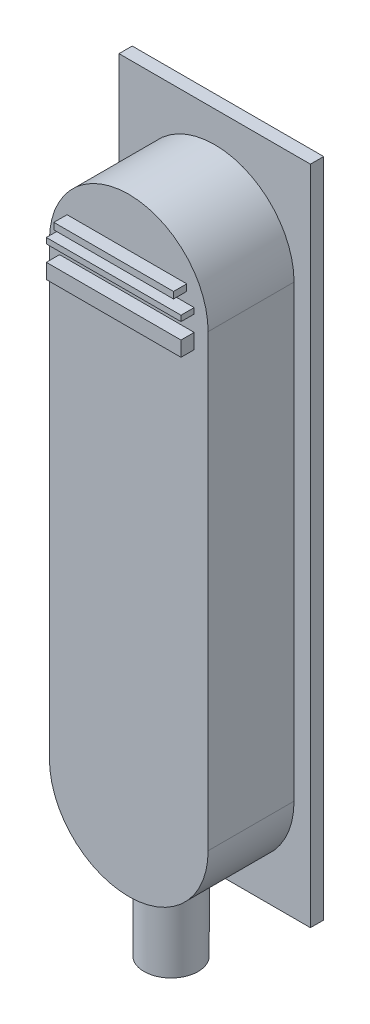
SolidWorks part; units mm, degrees
ref_plane "Front Plane" through (0, 0, 0) normal (0, 0, 1) x (1, 0, 0)
ref_plane "Top Plane" through (0, 0, 0) normal (0, 1, 0) x (1, 0, 0)
ref_plane "Right Plane" through (0, 0, 0) normal (1, 0, 0) x (0, 0, -1)
sketch "Sketch1" plane through (0, 0, 0) normal (0, 0, 1) x (1, 0, 0)
  line L1 (7.2385, -25.006) -> (-7.2385, -25.006)
  line L2 (7.2385, -25.006) -> (7.2385, 25.006)
  line L3 (7.2385, 25.006) -> (-7.2385, 25.006)
  line L4 (-7.2385, -25.006) -> (-7.2385, 25.006)
  line L5 (7.2385, -25.006) -> (-7.2385, 25.006) construction
  line L6 (7.2385, 25.006) -> (-7.2385, -25.006) construction
  point P0 (0, 0)
extrude "Boss-Extrude1" add sketch "Sketch1" along normal blind 1
sketch "Sketch2" plane through (0, 0, 1) normal (0, 0, 1) x (1, 0, 0)
  line L0 (0, 16.6654) -> (0, -17.3346) construction
  line L1 (6, 16.6654) -> (6, -17.3346)
  line L2 (-6, 16.6654) -> (-6, -17.3346)
  arc A0 (6, 16.6654) -> (-6, 16.6654) centre (0, 16.6654) ccw
  arc A1 (-6, -17.3346) -> (6, -17.3346) centre (0, -17.3346) ccw
  point P3 (0, -0.3346)
  point P8 (0, -23.3346)
  point P9 (0, 22.6654)
  dimension "D1" = 12
  dimension "D2" = 46
extrude "Boss-Extrude2" add sketch "Sketch2" along normal blind 6.5
sketch "Sketch4" plane through (0, 0, 7.5) normal (0, 0, 1) x (1, 0, 0)
  line L1 (-4.6671, 18.9912) -> (4.3843, 18.9912)
  line L2 (-4.6671, 18.9912) -> (-4.6671, 18.4962)
  line L3 (-4.6671, 18.4962) -> (4.3843, 18.4962)
  line L4 (4.3843, 18.9912) -> (4.3843, 18.4962)
  line L5 (-5.2328, 17.7183) -> (4.95, 17.7183)
  line L6 (-5.2328, 17.7183) -> (-5.2328, 17.294)
  line L7 (-5.2328, 17.294) -> (4.95, 17.294)
  line L8 (4.95, 17.7183) -> (4.95, 17.294)
  line L9 (-5.2328, 16.0919) -> (4.95, 16.0919)
  line L10 (-5.2328, 16.0919) -> (-5.2328, 14.9605)
  line L11 (-5.2328, 14.9605) -> (4.95, 14.9605)
  line L12 (4.95, 16.0919) -> (4.95, 14.9605)
extrude "Boss-Extrude4" add sketch "Sketch4" along normal blind 1
scale "Scale1" scale about centroid uniform scaling yes scale factor 0.5
scale "Scale2" scale about centroid uniform scaling yes scale factor 0.5
ref_plane "Plane1" through (0, -6, 0) normal (0, 1, 0) x (1, 0, 0)
sketch "Sketch5" plane through (0, -6, 0) normal (0, 1, 0) x (1, 0, 0)
  circle A0 centre (0, -3.7842) radius 0.5112
extrude "Boss-Extrude5" add sketch "Sketch5" against normal blind 1.35 separate body
sketch "Sketch7" plane through (0, -6, 0) normal (0, 1, 0) x (1, 0, 0)
  circle A0 centre (0, -3.7842) radius 0.5112
extrude "Boss-Extrude6" add sketch "Sketch7" along normal blind 1.35
